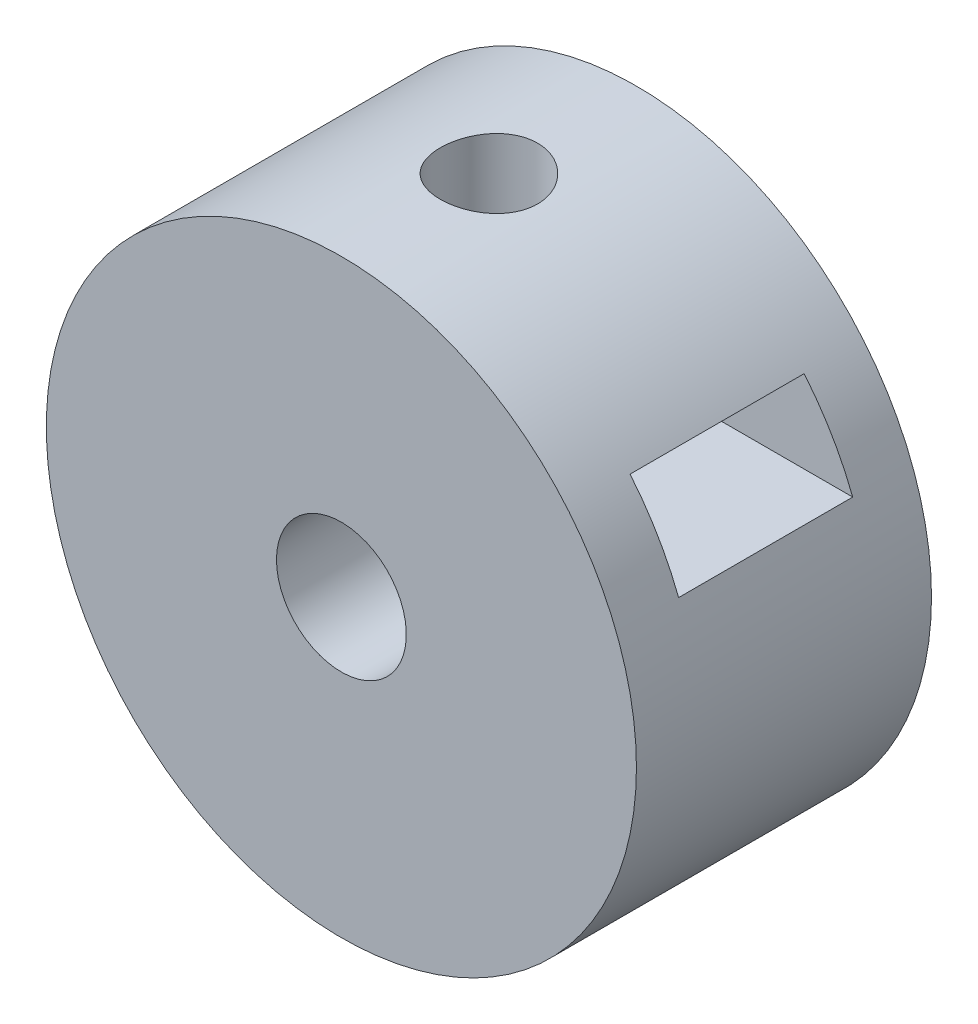
SolidWorks part; units mm, degrees
ref_plane "Спереди" through (0, 0, 0) normal (0, 0, 1) x (1, 0, 0)
ref_plane "Сверху" through (0, 0, 0) normal (0, 1, 0) x (1, 0, 0)
ref_plane "Справа" through (0, 0, 0) normal (1, 0, 0) x (0, 0, -1)
sketch "Эскиз1" plane through (0, 0, 0) normal (0, 0, 1) x (1, 0, 0)
  circle A0 centre (0, 0) radius 10
  dimension "D1" = 20
extrude "Бобышка-Вытянуть1" add sketch "Эскиз1" along normal blind 10
sketch "Эскиз2" plane through (0, 0, 0) normal (0, 0, -1) x (-1, 0, 0)
  circle A0 centre (0, 0) radius 2.2
  dimension "D1" = 4.4
extrude "Вырез-Вытянуть2" cut sketch "Эскиз2" against normal blind 10
ref_plane "Плоскость4" through (10, 0, 0) normal (1, 0, 0) x (0, 0, -1)
sketch3d "Трехмерный эскиз4"
  line L1 (10, 6.4, 7.9) -> (10, 6.4, 2)
  line L2 (10, 6.4, 7.9) -> (10, 3.6, 7.9)
  line L3 (10, 3.6, 7.9) -> (10, 3.6, 2)
  line L4 (10, 6.4, 2) -> (10, 3.6, 2)
  circle A0 centre (0, 0, 10) radius 2.2 construction
  point P6 (0, 0, 7.8)
  point P7 (10, 0, 10)
  point P8 (10, 5, 7.9)
  point P9 (10, 0, 10)
  dimension "D1" = 2.8
  dimension "D2" = 5.9
  dimension "D3" = 2.1
  dimension "D4" = 3.6
extrude "Вырез-Вытянуть3" cut sketch "Трехмерный эскиз4" along direction (1, 0, 0) on the side against the normal blind 10
ref_plane "Плоскость5" through (0, 10, 0) normal (0, 1, 0) x (1, 0, 0)
sketch "Эскиз5" plane through (0, 10, 0) normal (0, 1, 0) x (1, 0, 0)
  line L0 (10, 0) -> (-10, 0) construction
  circle A0 centre (0, -5) radius 1.65
  dimension "D1" = 3.3
  dimension "D2" = 5
extrude "Вырез-Вытянуть4" cut sketch "Эскиз5" against normal blind 10
sketch "Эскиз6" plane through (0, 10, 0) normal (0, 1, 0) x (1, 0, 0)
  line L1 (-1.7032, -2.05) -> (-3.4064, -5)
  line L2 (-3.4064, -5) -> (-1.7032, -7.95)
  line L3 (-1.7032, -7.95) -> (1.7032, -7.95)
  line L4 (1.7032, -7.95) -> (3.4064, -5)
  line L5 (3.4064, -5) -> (1.7032, -2.05)
  line L6 (1.7032, -2.05) -> (-1.7032, -2.05)
  line L7 (3.4064, -5) -> (-3.4064, -5) construction
  line L8 (7.6837, -2) -> (7.6837, -7.9) construction
  circle A0 centre (0, -5) radius 2.95 construction
  dimension "D1" = 5.9
  dimension "D2" = 5
extrude "Вырез-Вытянуть5" cut sketch "Эскиз6" along direction (0, 1, 0) on the side against the normal blind 2.8 from offset 3.6 contours L1 L2 L3 L4 L5 L6 offset against normal yes
